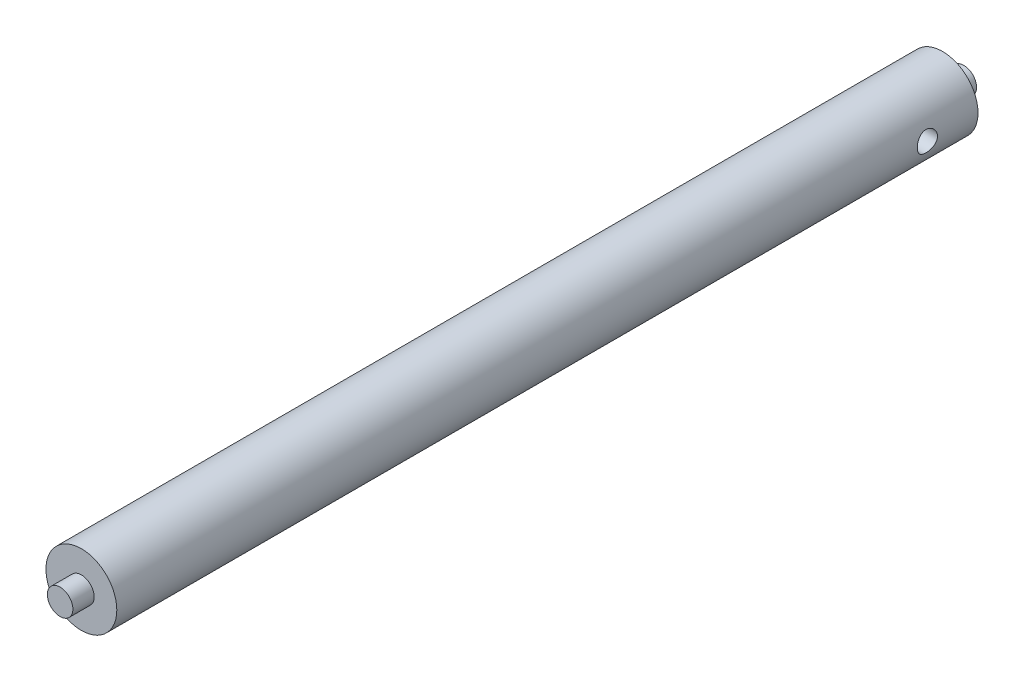
SolidWorks part; units mm, degrees
ref_plane "Plan de face" through (0, 0, 0) normal (0, 0, 1) x (1, 0, 0)
ref_plane "Plan de dessus" through (0, 0, 0) normal (0, 1, 0) x (1, 0, 0)
ref_plane "Plan de droite" through (0, 0, 0) normal (1, 0, 0) x (0, 0, -1)
sketch "Esquisse1" plane through (0, 0, 0) normal (0, 0, 1) x (1, 0, 0)
  circle A1 centre (0, 0) radius 50
  dimension "D2" = 100
extrude "Boss.-Extru.1" add sketch "Esquisse1" along normal blind 1215
sketch "Esquisse2" plane through (0, 0, 0) normal (0, 0, -1) x (-1, 0, 0)
  circle A0 centre (0, 0) radius 18
  dimension "D1" = 36
extrude "Boss.-Extru.2" add sketch "Esquisse2" along normal blind 30
sketch "Esquisse3" plane through (0, 0, 1215) normal (0, 0, 1) x (1, 0, 0)
  circle A0 centre (0, 0) radius 18
  dimension "D1" = 36
extrude "Boss.-Extru.3" add sketch "Esquisse3" along normal blind 30
sketch "Esquisse6" plane through (0, 0, 0) normal (1, 0, 0) x (0, 0, -1)
  line L0 (-71.4, 0) -> (0, 0) construction
  circle A0 centre (-71.4, 0) radius 14.3
  dimension "D2" = 28.6
  dimension "D1" = 71.4
extrude "Enlèv. mat.-Extru.1" cut sketch "Esquisse6" against normal through all and the other way through all
